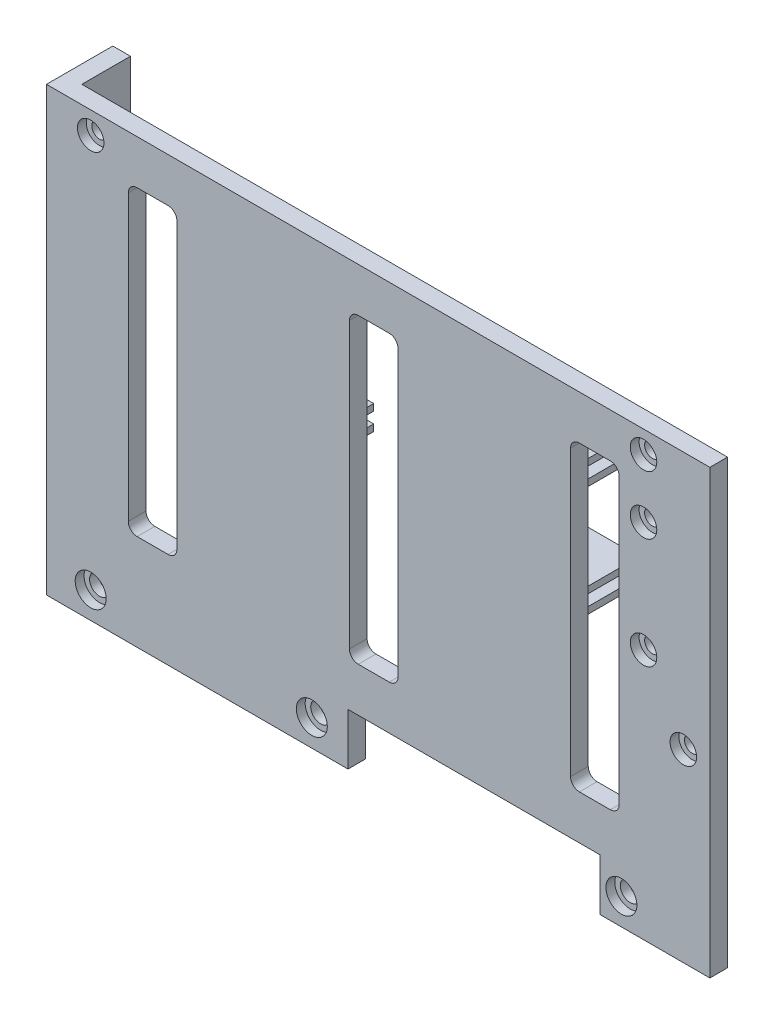
SolidWorks part; units mm, degrees
ref_plane "Front Plane" through (0, 0, 0) normal (0, 0, 1) x (1, 0, 0)
ref_plane "Top Plane" through (0, 0, 0) normal (0, 1, 0) x (1, 0, 0)
ref_plane "Right Plane" through (0, 0, 0) normal (1, 0, 0) x (0, 0, -1)
sketch "Sketch1" plane through (0, 0, 0) normal (0, 1, 0) x (1, 0, 0)
  line L1 (-75, -60) -> (75, -60)
  line L2 (-75, -60) -> (-75, -56)
  line L3 (-75, -56) -> (75, -56)
  line L4 (75, -60) -> (75, -56)
  dimension "D1" = 4
extrude "Boss-Extrude1" add sketch "Sketch1" along normal blind 100 contours L1 L4 L3 L2
sketch "Sketch7" plane through (0, 0, 60) normal (0, 0, 1) x (1, 0, 0)
  line L0 (-75, 0) -> (75, 0) construction
  line L1 (-6.82, 0) -> (50.18, 0)
  line L2 (-6.82, 0) -> (-6.82, 11.6942)
  line L3 (-6.82, 11.6942) -> (50.18, 11.6942)
  line L4 (50.18, 0) -> (50.18, 11.6942)
  line L5 (75, 100) -> (75, 0) construction
  dimension "D1" = 24.82
  dimension "D2" = 57
extrude "Cut-Extrude1" cut sketch "Sketch7" against normal up to next
sketch "Sketch9" plane through (0, 0, 56) normal (0, 0, -1) x (-1, 0, 0)
  line L0 (75, 0) -> (6.82, 0) construction
  line L1 (75, 100) -> (71, 100)
  line L2 (75, 100) -> (75, 0)
  line L3 (75, 0) -> (71, 0)
  line L4 (71, 100) -> (71, 0)
  dimension "D1" = 4
extrude "Boss-Extrude4" add sketch "Sketch9" along normal blind 11
sketch "Sketch10" plane through (0, 0, 56) normal (0, 0, -1) x (-1, 0, 0)
  line L0 (71, 0) -> (6.82, 0) construction
  line L1 (-40, 51.5) -> (-20, 51.5)
  line L2 (-40, 51.5) -> (-40, 50)
  line L3 (-40, 50) -> (-20, 50)
  line L4 (-20, 51.5) -> (-20, 50)
  line L5 (-75, 100) -> (-75, 0) construction
  dimension "D1" = 50
  dimension "D2" = 1.5
  dimension "D3" = 35
  dimension "D4" = 20
extrude "Boss-Extrude5" add sketch "Sketch10" along normal blind 15
pattern_linear "LPattern1" count 2 spacing 60 along (-1, 0, 0) of "Boss-Extrude5"
pattern_linear "LPattern2" count 2 spacing 25 along (0, 1, 0) of "LPattern1", "Boss-Extrude5"
pattern_linear "LPattern3" count 2 spacing 4 along (0, 1, 0) of "LPattern2", "Boss-Extrude5", "LPattern1"
sketch "Sketch12" plane through (0, 0, 60) normal (0, 0, 1) x (1, 0, 0)
  line L0 (-75, 100) -> (-75, 0) construction
  line L1 (-75, 0) -> (-6.82, 0) construction
  circle A0 centre (-65, 6) radius 3.5
  dimension "D1" = 10
  dimension "D2" = 6
extrude "Cut-Extrude2" cut sketch "Sketch12" against normal blind 2
sketch "Sketch13" plane through (0, 0, 58) normal (0, 0, 1) x (1, 0, 0)
  circle A0 centre (-65, 6) radius 2.25
extrude "Cut-Extrude3" cut sketch "Sketch13" against normal up to next
pattern_linear "LPattern4" count 2 spacing 50 along (1, 0, 0) of "Cut-Extrude3", "Cut-Extrude2"
sketch "Sketch15" plane through (125.7781, 81.4036, 60) normal (0, 0, 1) x (1, 0, 0)
  line L2 (-200.7781, 18.5964) -> (-50.7781, 18.5964) construction
  line L4 (-50.7781, 18.5964) -> (-50.7781, -81.4036) construction
  circle A0 centre (-65.7781, 0.3464) radius 3
  dimension "D1" = 18.25
  dimension "D2" = 15
extrude "Cut-Extrude4" cut sketch "Sketch15" against normal blind 2
sketch "Sketch17" plane through (125.7781, 81.4036, 58) normal (0, 0, 1) x (1, 0, 0)
  circle A0 centre (-65.7781, 0.3464) radius 1.75
extrude "Cut-Extrude5" cut sketch "Sketch17" against normal up to next
pattern_linear "LPattern5" count 2 spacing 25 along (0, -1, 0) of "Cut-Extrude5", "Cut-Extrude4"
sketch "Sketch18" plane through (0, 0, 56) normal (0, 0, -1) x (-1, 0, 0)
  line L0 (71, 100) -> (-75, 100) construction
  line L1 (-72.5, 90) -> (-62.5, 90)
  line L2 (-72.5, 90) -> (-72.5, 83)
  line L3 (-72.5, 83) -> (-62.5, 83)
  line L4 (-62.5, 90) -> (-62.5, 83)
  line L5 (-75, 100) -> (-75, 0) construction
  dimension "D1" = 10
  dimension "D2" = 2.5
  dimension "D3" = 7
  dimension "D4" = 10
extrude "Cut-Extrude6" cut sketch "Sketch18" against normal blind 3
pattern_linear "LPattern6" count 2 spacing 55 along (0, -1, 0) of "Cut-Extrude6"
sketch "Sketch19" plane through (0, 0, 56) normal (0, 0, -1) x (-1, 0, 0)
  line L0 (71, 100) -> (-75, 100) construction
  line L1 (-54.5, 90) -> (-43.5, 90)
  line L2 (-54.5, 90) -> (-54.5, 21.6942)
  line L3 (-54.5, 21.6942) -> (-43.5, 21.6942)
  line L4 (-43.5, 90) -> (-43.5, 21.6942)
  line L5 (-50.18, 11.6942) -> (6.82, 11.6942) construction
  line L6 (-75, 100) -> (-75, 0) construction
  dimension "D1" = 10
  dimension "D2" = 10
  dimension "D3" = 11
  dimension "D4" = 20.5
extrude "Cut-Extrude7" cut sketch "Sketch19" against normal up to next
fillet "Fillet1" radius 2 4 edges at (43.5, 21.6942, 58) (54.5, 21.6942, 58) (54.5, 90, 58) (43.5, 90, 58)
pattern_linear "LPattern7" count 3 spacing 50 along (-1, 0, 0) of "Cut-Extrude7", "Fillet1"
pattern_linear "LPattern8" count 2 spacing 120 along (1, 0, 0) of "Cut-Extrude2", "Cut-Extrude3"
sketch "Sketch20" plane through (0, 0, 56) normal (0, 0, -1) x (-1, 0, 0)
  line L0 (-75, 100) -> (-75, 0) construction
  line L1 (-33, 94.135) -> (-25, 94.135)
  line L2 (-33, 94.135) -> (-33, 84.135)
  line L3 (-33, 84.135) -> (-25, 84.135)
  line L4 (-25, 94.135) -> (-25, 84.135)
  dimension "D1" = 8
  dimension "D2" = 10
  dimension "D3" = 42
extrude "Cut-Extrude8" cut sketch "Sketch20" against normal blind 3
pattern_linear "LPattern9" count 2 spacing 60 along (-1, 0, 0) of "Cut-Extrude8"
sketch "Sketch22" plane through (131.1673, 38.9382, 60) normal (0, 0, 1) x (1, 0, 0)
  line L3 (-56.1673, 61.0618) -> (-56.1673, -38.9382) construction
  circle A0 centre (-62.1673, 2.8118) radius 3
  circle A1 centre (-71.1673, 17.8118) radius 1.75 construction
  point P8 (-56.1673, 18.2733)
  dimension "D1" = 15
  dimension "D2" = 6
extrude "Cut-Extrude9" cut sketch "Sketch22" against normal blind 2
sketch "Sketch24" plane through (131.1673, 38.9382, 58) normal (0, 0, 1) x (1, 0, 0)
  circle A0 centre (-62.1673, 2.8118) radius 1.75
extrude "Cut-Extrude10" cut sketch "Sketch24" against normal up to next
sketch "Sketch26" plane through (-1.5552, 92.3917, 60) normal (0, 0, 1) x (1, 0, 0)
  line L0 (-73.4448, 7.6083) -> (-73.4448, -92.3917) construction
  line L1 (-73.4448, 7.6083) -> (76.5552, 7.6083) construction
  circle A0 centre (-63.4448, 2.6083) radius 3
  point P8 (-56.1673, 18.2733)
  dimension "D1" = 10
  dimension "D2" = 5
extrude "Cut-Extrude11" cut sketch "Sketch26" against normal blind 2
sketch "Sketch28" plane through (-1.5552, 92.3917, 58) normal (0, 0, 1) x (1, 0, 0)
  circle A0 centre (-63.4448, 2.6083) radius 1.75
extrude "Cut-Extrude12" cut sketch "Sketch28" against normal up to next
pattern_linear "LPattern11" count 2 spacing 125 along (1, 0, 0) of "Cut-Extrude12", "Cut-Extrude11"
